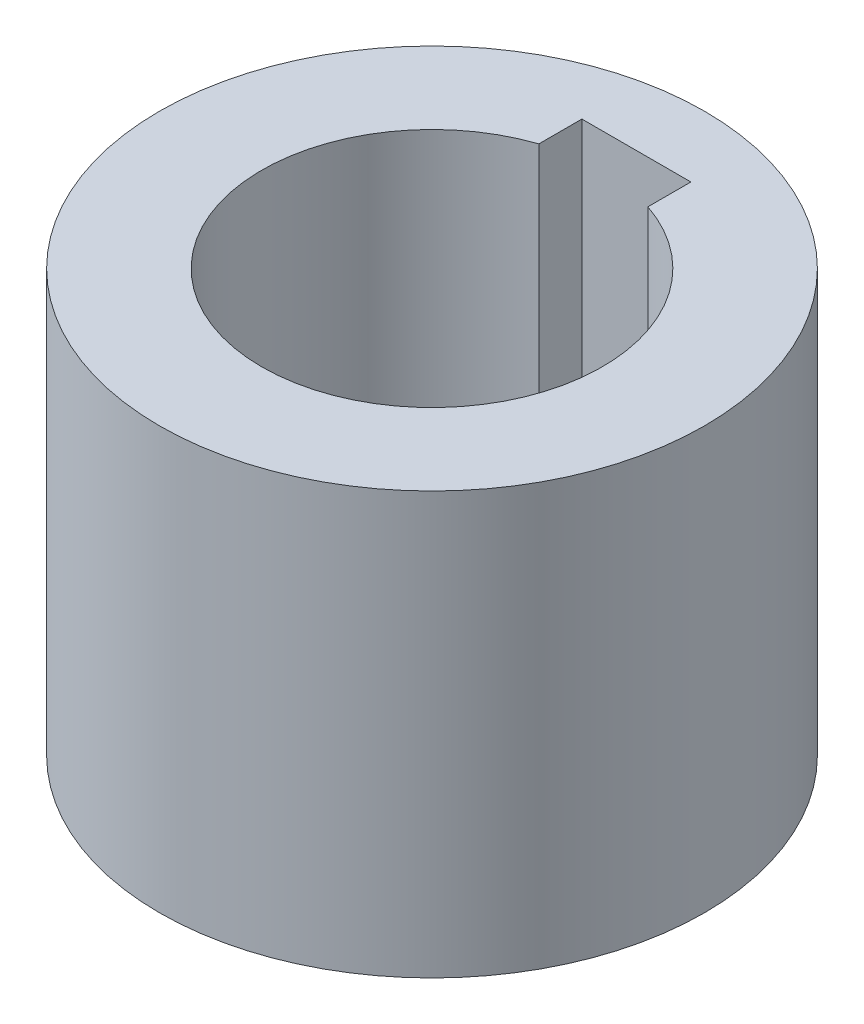
SolidWorks part; units mm, degrees
material "ASTM A36 Steel"
ref_plane "Front Plane" through (0, 0, 0) normal (0, 0, 1) x (1, 0, 0)
ref_plane "Top Plane" through (0, 0, 0) normal (0, 1, 0) x (1, 0, 0)
ref_plane "Right Plane" through (0, 0, 0) normal (1, 0, 0) x (0, 0, -1)
sketch "Sketch1" plane through (0, 0, 0) normal (0, 1, 0) x (1, 0, 0)
  circle A0 centre (0, 0) radius 25
  circle A1 centre (0, 0) radius 40
  dimension "D1" = 80
  dimension "D2" = 50
extrude "Boss-Extrude1" add sketch "Sketch1" along normal blind 61.9
sketch "Sketch2" plane through (0, 61.9, 0) normal (0, 1, 0) x (1, 0, 0)
  line L1 (-8, 20) -> (8, 20)
  line L2 (-8, 20) -> (-8, 30)
  line L3 (-8, 30) -> (8, 30)
  line L4 (8, 20) -> (8, 30)
  line L5 (-8, 20) -> (8, 30) construction
  line L6 (-8, 30) -> (8, 20) construction
  circle A0 centre (0, 0) radius 25 construction
  point P0 (0, 25)
  dimension "D1" = 16
  dimension "D2" = 10
extrude "Cut-Extrude1" cut sketch "Sketch2" against normal through all both and the other way through all
